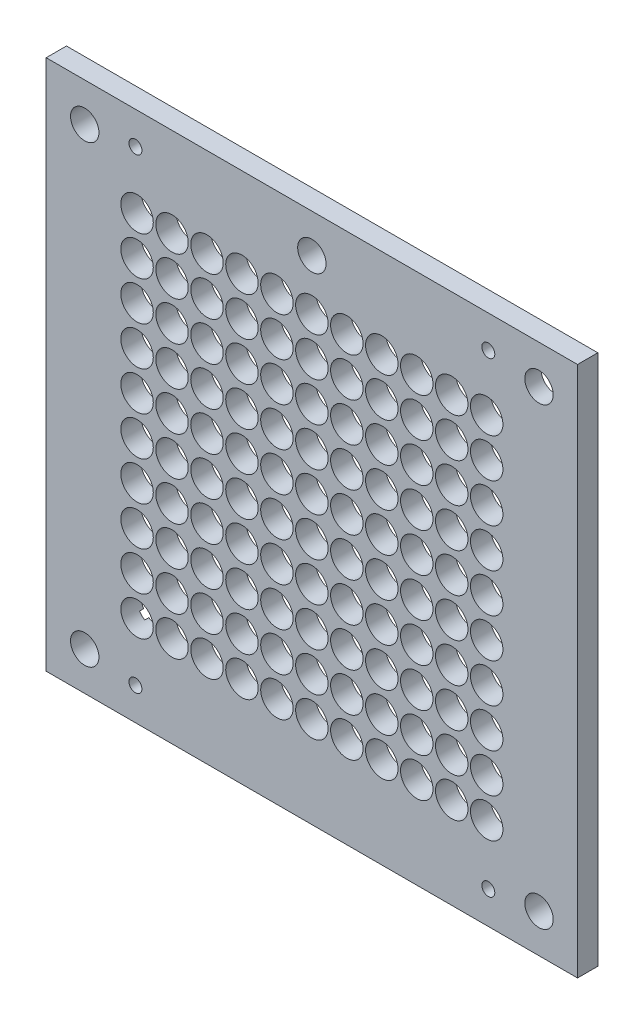
SolidWorks part; units mm, degrees
ref_plane "Ebene vorne" through (0, 0, 0) normal (0, 0, 1) x (1, 0, 0)
ref_plane "Ebene oben" through (0, 0, 0) normal (0, 1, 0) x (1, 0, 0)
ref_plane "Ebene rechts" through (0, 0, 0) normal (1, 0, 0) x (0, 0, -1)
sketch "Skizze2" plane through (0, 0, 0) normal (0, 0, 1) x (1, 0, 0)
  line L0 (-65.5, 65.5) -> (-65.5, -65.5) construction
  line L1 (-65.5, -65.5) -> (65.5, -65.5) construction
  line L2 (65.5, 65.5) -> (-65.5, 65.5) construction
  line L3 (65.5, -65.5) -> (65.5, 65.5) construction
  line L4 (-65.5, 65.5) -> (-65.5, -65.5)
  line L5 (-65.5, -65.5) -> (65.5, -65.5)
  line L6 (65.5, 65.5) -> (-65.5, 65.5)
  line L7 (65.5, -65.5) -> (65.5, 65.5)
extrude "Aufsatz-Linear austragen1" add sketch "Skizze2" along normal blind 5
sketch "Skizze3" plane through (0, 0, 0) normal (0, 0, -1) x (-1, 0, 0)
  line L0 (0, 65.5) -> (0, 0) construction
  line L1 (-65.5, 65.5) -> (65.5, 65.5) construction
  line L2 (-67.5, 67.5) -> (67.5, 67.5) construction
  circle A0 centre (0, 56) radius 3.5
  dimension "D1" = 7
  dimension "D2" = 11.5
extrude "Schnitt-Linear austragen1" cut sketch "Skizze3" against normal up to surface (5 mm away) up to face at (0, 0, 5)
sketch "Skizze4" plane through (0, 0, 0) normal (0, 0, -1) x (-1, 0, 0)
  line L0 (0, 0) -> (0, 65.5) construction
  line L1 (-65.5, 65.5) -> (65.5, 65.5) construction
  line L2 (-67.5, 67.5) -> (67.5, 67.5) construction
  circle A0 centre (0, 43.5) radius 4
  dimension "D1" = 8
  dimension "D2" = 24
extrude "Schnitt-Linear austragen2" cut sketch "Skizze4" against normal up to surface (5 mm away) up to face at (3.5, 56, 5)
pattern_linear "Lineares Muster1" count 6 spacing 8.62 along (1, 0, 0) count 10 spacing 9.6111 along (0, -1, 0) of "Schnitt-Linear austragen2"
pattern_linear "Lineares Muster2" count 6 spacing 8.62 along (-1, 0, 0) count 10 spacing 9.6111 along (0, -1, 0) skipping (0, 1), (0, 2), (0, 3), (0, 4), (0, 5), (0, 6), (0, 7), (0, 8), (0, 9) of "Schnitt-Linear austragen2"
sketch "Skizze5" plane through (0, 0, 0) normal (0, 0, -1) x (-1, 0, 0)
  line L0 (-67.5, -67.5) -> (-67.5, 67.5) construction
  line L1 (-67.5, 67.5) -> (67.5, 67.5) construction
  line L2 (67.5, 67.5) -> (67.5, -67.5) construction
  line L3 (67.5, -67.5) -> (-67.5, -67.5) construction
  circle A0 centre (-50, 50) radius 6
  circle A1 centre (50, 50) radius 6
  circle A2 centre (-50, -50) radius 6
  circle A3 centre (50, -50) radius 6
  dimension "D1" = 12
  dimension "D3" = 17.5
  dimension "D4" = 12
  dimension "D5" = 17.5
  dimension "D6" = 17.5
  dimension "D7" = 12
  dimension "D8" = 12
  dimension "D9" = 17.5
  dimension "D10" = 17.5
  dimension "D11" = 17.5
  dimension "D12" = 17.5
  dimension "D2" = 17.5
extrude "Schnitt-Linear austragen3" cut sketch "Skizze5" against normal blind 1
sketch "Skizze6" plane through (0, 0, 0) normal (0, 0, -1) x (-1, 0, 0)
  line L0 (-67.5, -67.5) -> (-67.5, 67.5) construction
  line L1 (-67.5, 67.5) -> (67.5, 67.5) construction
  line L2 (67.5, -67.5) -> (-67.5, -67.5) construction
  line L3 (67.5, 67.5) -> (67.5, -67.5) construction
  circle A0 centre (-56, 56) radius 3.5
  circle A1 centre (-56, -56) radius 3.5
  circle A2 centre (56, -56) radius 3.5
  circle A3 centre (56, 56) radius 3.5
  dimension "D1" = 7
  dimension "D2" = 11.5
  dimension "D3" = 11.5
  dimension "D4" = 7
  dimension "D5" = 7
  dimension "D6" = 7
  dimension "D7" = 11.5
  dimension "D8" = 11.5
  dimension "D9" = 11.5
  dimension "D11" = 11.5
  dimension "D12" = 11.5
  dimension "D10" = 11.5
extrude "Schnitt-Linear austragen4" cut sketch "Skizze6" against normal up to surface (5 mm away) up to face at (-39.1, -43, 5)
sketch "Skizze7" plane through (0, 0, 1) normal (0, 0, -1) x (-1, 0, 0)
  circle A0 centre (-50, 50) radius 3
  circle A1 centre (50, 50) radius 3
  circle A2 centre (50, -50) radius 3
  circle A3 centre (-50, -50) radius 3
extrude "Schnitt-Linear austragen5" cut sketch "Skizze7" against normal blind 1.2
hole_wizard "Formsenkung für M3 Senkschraube mit Innensechskant1" positions "Skizze10" profile "Skizze11" countersink size "M3" standard "DIN"
sketch "Skizze10" plane through (0, 0, 0) normal (0, 0, -1) x (-1, 0, 0)
  point P0 (-43.5, 57.5)
  point P3 (43.5, 57.5)
  point P6 (43.5, -57.5)
  point P9 (-43.5, -57.5)
sketch "Skizze11" plane through (43.5, 57.5, 0) normal (1, 0, 0) x (0, 1, 0)
  line L0 (0, 0) -> (0, 5.9604)
  line L1 (0, 5.9604) -> (1.6, 4.999)
  line L2 (1.6, 4.999) -> (1.6, 2.37)
  line L3 (1.6, 2.37) -> (3.97, 0)
  line L4 (3.97, 0) -> (0, 0)
  line L5 (-1.6, 2.37) -> (-3.97, 0) construction
  line L6 (0, 5.9604) -> (-1.6, 4.999) construction
  line L7 (0, -6.35) -> (0, 107.95) construction
  dimension "Bohrerdurchmesser" = 3.2
  dimension "Bohrungstiefe" = 4.999
  dimension "Senkdurchmesser (Oben)" = 7.94
  dimension "Senkwinkel (Oben)" = 90
  dimension "Spitzenwinkel" = 118
